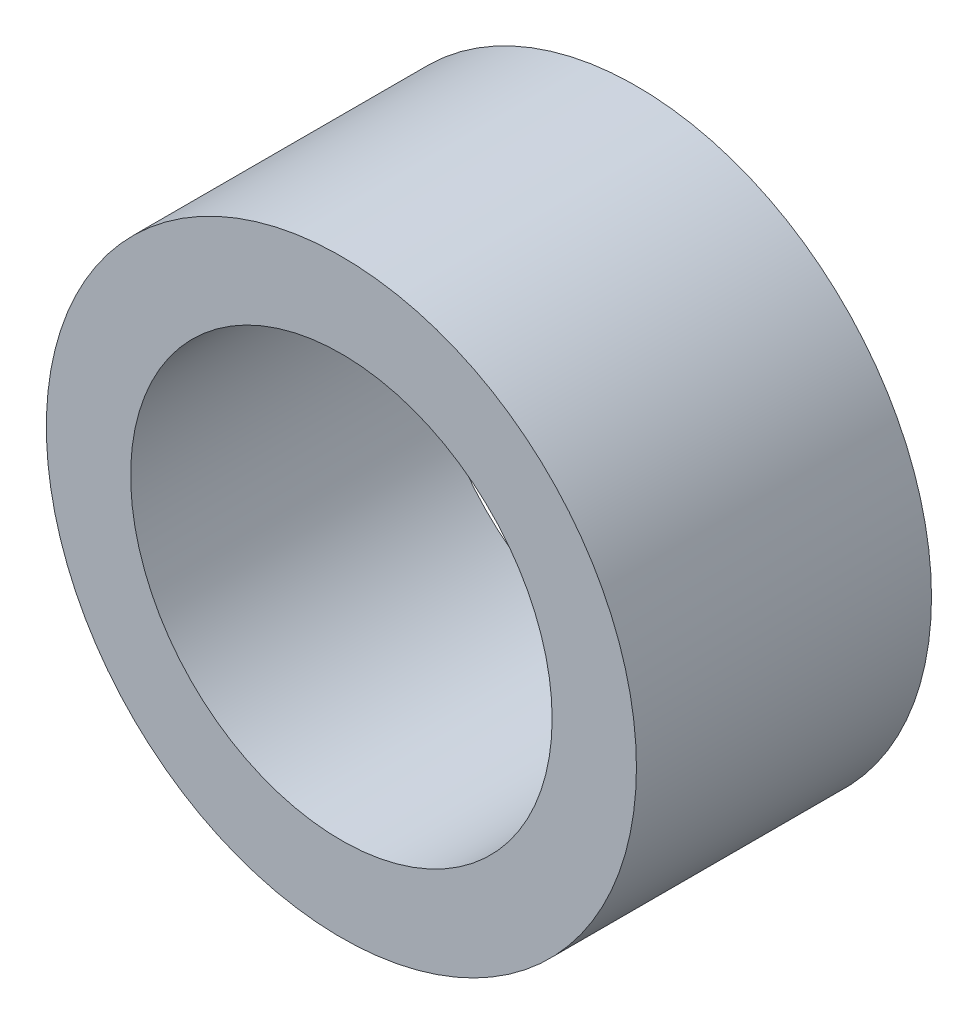
SolidWorks part; units mm, degrees
ref_plane "Front Plane" through (0, 0, 0) normal (0, 0, 1) x (1, 0, 0)
ref_plane "Top Plane" through (0, 0, 0) normal (0, 1, 0) x (1, 0, 0)
ref_plane "Right Plane" through (0, 0, 0) normal (1, 0, 0) x (0, 0, -1)
sketch "Sketch1" plane through (0, 0, 0) normal (0, 0, 1) x (1, 0, 0)
  circle A0 centre (0, 0) radius 2.5
  circle A1 centre (0, 0) radius 3.5
  dimension "D1" = 5
  dimension "D2" = 7
extrude "Boss-Extrude1" add sketch "Sketch1" along normal blind 3.5
